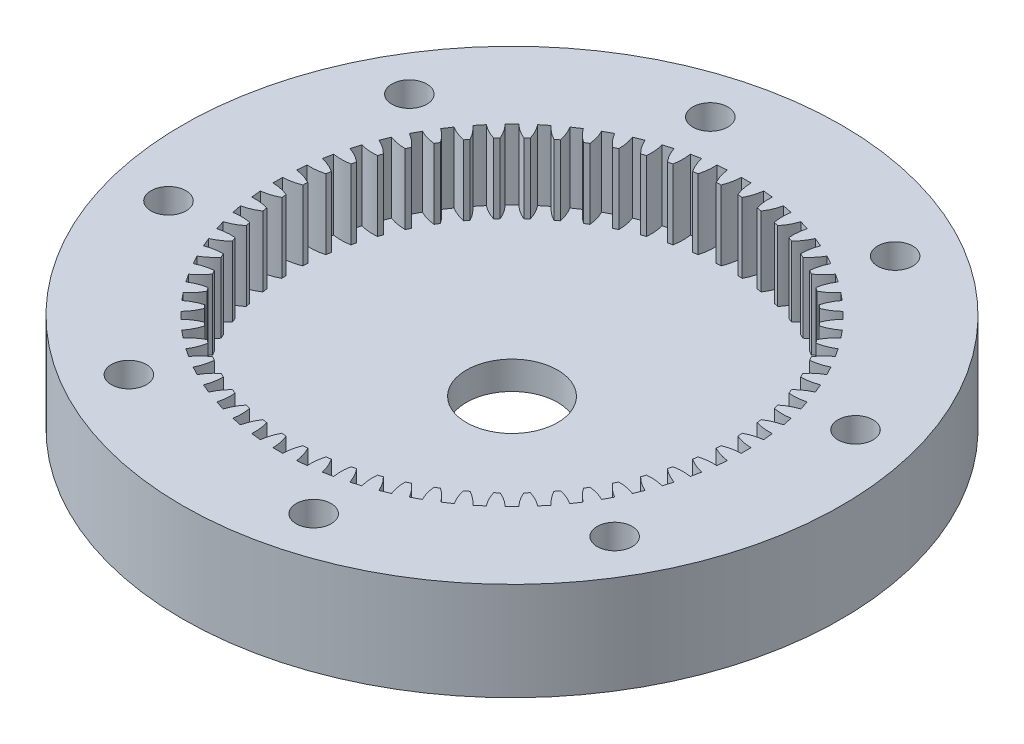
SolidWorks part; units mm, degrees
ref_plane "Front Plane" through (0, 0, 0) normal (0, 0, 1) x (1, 0, 0)
ref_plane "Top Plane" through (0, 0, 0) normal (0, 1, 0) x (1, 0, 0)
ref_plane "Right Plane" through (0, 0, 0) normal (1, 0, 0) x (0, 0, -1)
sketch "Sketch1" plane through (0, 0, 0) normal (0, 1, 0) x (1, 0, 0)
  circle A0 centre (0, 0) radius 16
  circle A1 centre (0, 0) radius 16.7
  circle A2 centre (0, 0) radius 15.5
  dimension "D1" = 32
  dimension "D2" = 33.4
  dimension "D3" = 1.2
extrude "Boss-Extrude1" add sketch "Sketch1" along normal mid plane 5 contours A1 A0 | A0 A2 | A2
sketch "Sketch7" plane through (0, 0, 0) normal (0, 1, 0) x (1, 0, 0)
  line L0 (16.7, 0) -> (-16.7, 0) construction
  line L1 (0, 16.7) -> (0, -16.7) construction
  circle A0 centre (0, 0) radius 16.7 construction
  point P7 (0, 0)
sketch "Sketch4" plane through (0, 0, 0) normal (0, 1, 0) x (1, 0, 0)
  line L0 (0, 0) -> (0, -23.5) construction
  line L10 (0, 0) -> (20.3516, 11.75) construction
  circle A2 centre (0, 0) radius 15.5 construction
  circle A3 centre (0, 0) radius 15.5
  circle A9 centre (0, 0) radius 23.5
  dimension "D3" = 120
extrude "Boss-Extrude2" add sketch "Sketch4" along normal mid plane 5
sketch "Sketch3" plane through (0, 0, 0) normal (0, 1, 0) x (1, 0, 0)
  line L0 (0, 0) -> (0, 16.7) construction
  line L1 (-0.3927, 15.9952) -> (0.3927, 15.9952) construction
  line L2 (-0.3434, 15.4962) -> (0, 0) construction
  line L3 (0, 13.7683) -> (-0.5155, 16.692) construction
  line L4 (0, 0) -> (0.8194, 16.6799) construction
  line L5 (0.3927, 15.9952) -> (1.177, 15.9566) construction
  line L6 (0, 15.5) -> (0, 16.7) construction
  line L7 (0.3434, 15.4962) -> (0.3434, 16.7) construction
  line L8 (0.3434, 16.0981) -> (-0.3121, 16.0981) construction
  arc A1 (-0.5957, 16.6894) -> (-0.3434, 15.4962) centre (-3.6364, 15.4232) cw construction
  arc A2 (0.5957, 16.6894) -> (0.3434, 15.4962) centre (3.6364, 15.4232) ccw construction
  circle A3 centre (0, 0) radius 15.5 construction
  arc A4 (0.3434, 15.4962) -> (-0.3434, 15.4962) centre (0, 0) ccw construction
  circle A5 centre (0, 0) radius 16 construction
  circle A6 centre (0, 0) radius 16.7 construction
  arc A7 (0.5957, 15.5068) -> (-0.5957, 15.5068) centre (0, 32.1962) cw
  arc A8 (0.5957, 16.6894) -> (-0.5957, 16.6894) centre (0, 0) ccw construction
  arc A9 (-0.5957, 15.5068) -> (-0.3434, 16.7) centre (-3.6364, 16.773) ccw
  arc A10 (0.5957, 15.5068) -> (0.3434, 16.7) centre (3.6364, 16.773) cw
  arc A11 (0.3434, 16.7) -> (-0.3434, 16.7) centre (0, 32.1962) cw
  dimension "D3" = 2.813
  dimension "D2" = 10
extrude "Cut-Extrude1" cut sketch "Sketch3" against normal through all both and the other way through all
pattern_circular "CirPattern1" count 64 over 360 about axis through (0, 0, 0) along (0, 1, 0) of "Cut-Extrude1"
sketch "Sketch5" plane through (0, 0, 0) normal (0, 1, 0) x (1, 0, 0)
  circle A0 centre (0, 0) radius 15.5183
extrude "Cut-Extrude2" cut sketch "Sketch5" against normal through all both and the other way through all
sketch "Sketch8" plane through (0, -2.5, 0) normal (0, -1, 0) x (1, 0, 0)
  circle A0 centre (0, 0) radius 3.25
  circle A1 centre (0, 0) radius 23.5
  dimension "D2" = 6.5
extrude "Boss-Extrude3" add sketch "Sketch8" along normal blind 2
sketch "Sketch6" plane through (0, 2.5, 0) normal (0, 1, 0) x (1, 0, 0)
  line L0 (0, 0) -> (5.1764, -19.3185) construction
  line L2 (0, -16.7) -> (0, 16.7) construction
  circle A3 centre (5.1764, -19.3185) radius 1.25
  point P11 (0, 0)
  dimension "D2" = 15
  dimension "D1" = 2.5
  dimension "D3" = 20
extrude "Cut-Extrude3" cut sketch "Sketch6" against normal through all
pattern_circular "CirPattern2" count 8 over 360 about axis through (0, 0, 0) along (0, 1, 0) of "Cut-Extrude3"
equation "\"Module\"= .5"
equation "\"Number of Teeth\"=64"
equation "\"D1@Sketch1\"=\"Module\"* \"Number of Teeth\""
equation "\"D2@Sketch1\"=(\"Number of Teeth\" + 2) * \"Module\" + .4"
equation "\"D3@Sketch1\"=\"Module\" * if( \"Module\" => 1.25, 2.25, 2.4)"
equation "\"D3@Sketch3\"=180 / \"Number of Teeth\""
equation "\"D1@CirPattern1\"=\"Number of Teeth\""
